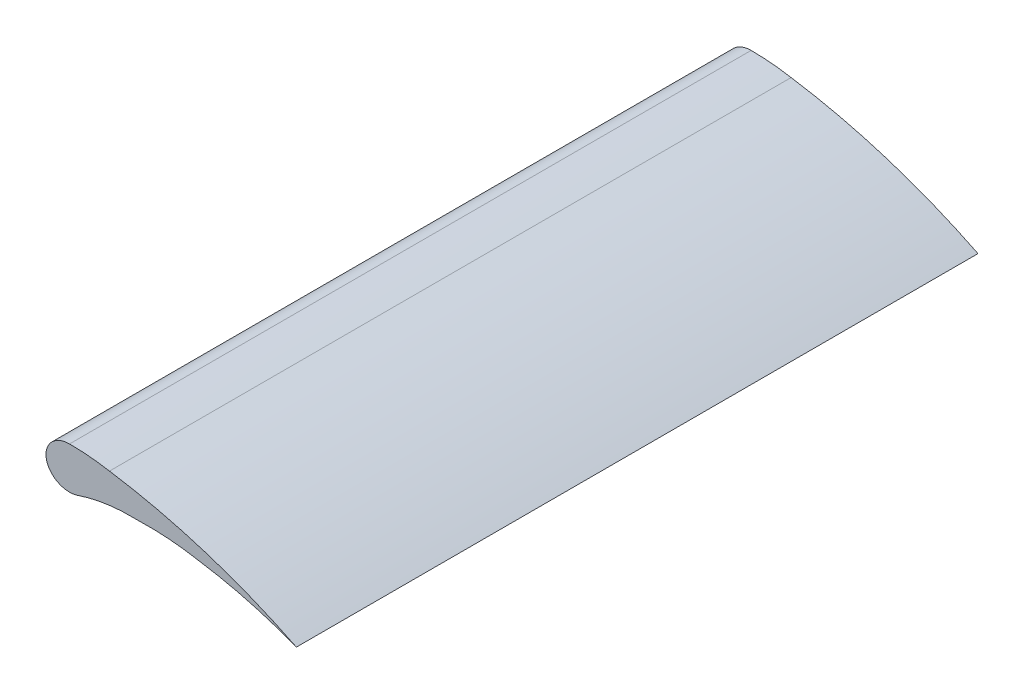
SolidWorks part; units mm, degrees
ref_plane "Front Plane" through (0, 0, 0) normal (0, 0, 1) x (1, 0, 0)
ref_plane "Top Plane" through (0, 0, 0) normal (0, 1, 0) x (1, 0, 0)
ref_plane "Right Plane" through (0, 0, 0) normal (1, 0, 0) x (0, 0, -1)
sketch "Sketch1" plane through (0, 0, 0) normal (0, 0, 1) x (1, 0, 0)
  arc A0 (5.9882, 4.1427) -> (16.1938, 5.6989) centre (15.6218, -24.793) cw
  arc A1 (11.8313, 10.9976) -> (46.6539, 0) centre (-6.4074, -107.3833) cw
  arc A2 (17.4361, 5.706) -> (28.5087, 4.8484) centre (18.9974, -46.0455) cw
  arc A3 (11.8313, 10.9976) -> (4.3813, 11.652) centre (4.3813, -31.0826) ccw
  arc A4 (16.1938, 5.6989) -> (17.4361, 5.706) centre (16.6701, 31.0944) ccw
  arc A6 (28.5087, 4.8484) -> (46.6539, 0) centre (16.0656, -78.0988) cw
  ellipse E0 centre (4.3813, 7.7618) end of major axis (0, 7.7618) minor radius 3.8902 (4.3813, 11.652) -> (5.9882, 4.1427) ccw
  dimension "D1" = 0
extrude "Boss-Extrude1" add sketch "Sketch1" against normal blind 127
